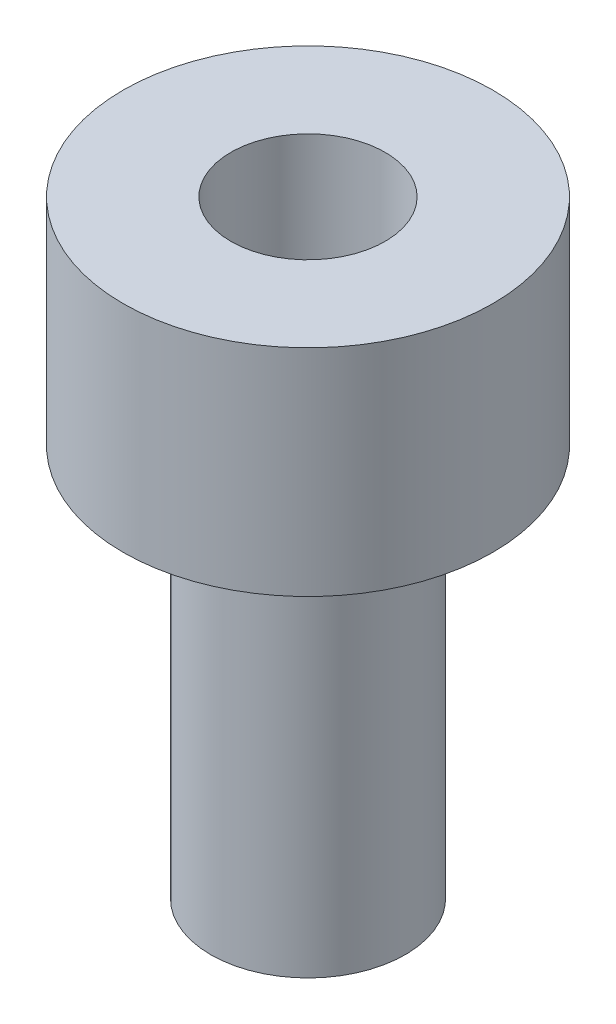
SolidWorks part; units mm, degrees
material "ABS"
ref_plane "Front Plane" through (0, 0, 0) normal (0, 0, 1) x (1, 0, 0)
ref_plane "Top Plane" through (0, 0, 0) normal (0, 1, 0) x (1, 0, 0)
ref_plane "Right Plane" through (0, 0, 0) normal (1, 0, 0) x (0, 0, -1)
sketch "Sketch1" plane through (0, 0, 0) normal (0, 1, 0) x (1, 0, 0)
  circle A0 centre (0, 0) radius 3.025
  dimension "D1" = 6.05
extrude "Boss-Extrude1" add sketch "Sketch1" along normal blind 12.2
sketch "Sketch2" plane through (0, 12.2, 0) normal (0, 1, 0) x (1, 0, 0)
  circle A0 centre (0, 0) radius 5.75
  circle A1 centre (0, 0) radius 2.4
  dimension "D1" = 11.5
  dimension "D2" = 4.8
extrude "Boss-Extrude2" add sketch "Sketch2" along normal blind 6.7 contours A1 | A0
sketch "Sketch3" plane through (0, 12.2, 0) normal (0, 1, 0) x (1, 0, 0)
  circle A1 centre (0, 0) radius 2.4
  circle A2 centre (0, 0) radius 2.4
  dimension "D1" = 0
extrude "Boss-Extrude3" add sketch "Sketch3" along normal blind 1.4
